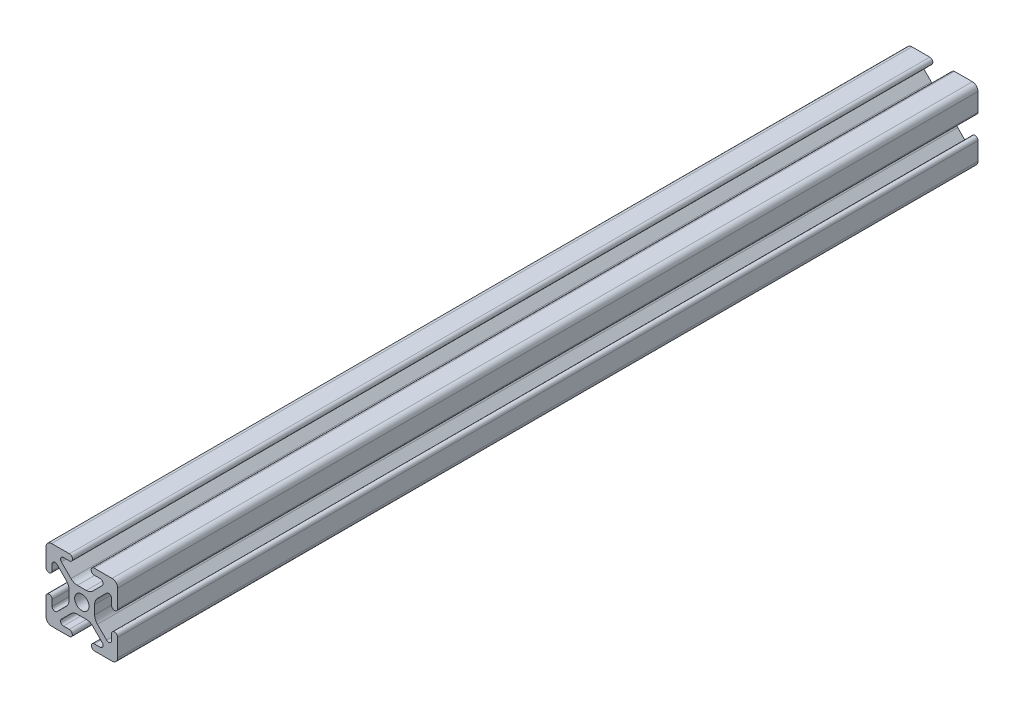
SolidWorks part; units mm, degrees
material "6005A-T61"
ref_plane "Front Plane" through (0, 0, 0) normal (0, 0, 1) x (1, 0, 0)
ref_plane "Top Plane" through (0, 0, 0) normal (0, 1, 0) x (1, 0, 0)
ref_plane "Right Plane" through (0, 0, 0) normal (1, 0, 0) x (0, 0, -1)
sketch "Sketch1" plane through (0, 0, 0) normal (0, 0, 1) x (1, 0, 0)
  line L0 (-8.6363, 7.1116) -> (-5.4322, 3.9121)
  line L1 (-4.455, 1.5554) -> (-4.455, -1.5554)
  line L2 (-5.4322, -3.9121) -> (-8.6363, -7.1116)
  line L3 (-10.36, -6.3969) -> (-10.36, -4.32)
  line L4 (-12.5, -4.32) -> (-12.5, -8.6518)
  line L5 (-12.5, -8.6518) -> (-12.5, -10.5371)
  line L6 (-10.5371, -12.5) -> (-8.4416, -12.5)
  line L7 (-8.4416, -12.5) -> (-4.3879, -12.5)
  line L8 (-4.3879, -10.36) -> (-6.42, -10.36)
  line L9 (-7.1337, -8.6353) -> (-3.7953, -5.3018)
  line L10 (-1.5554, -4.375) -> (1.5554, -4.375)
  line L11 (10.36, 4.32) -> (10.36, 6.3969)
  line L12 (12.5, 7.9913) -> (12.5, 4.32)
  line L13 (12.5, 10.5371) -> (12.5, 7.9913)
  line L14 (4.32, 12.5) -> (10.5371, 12.5)
  line L16 (6.42, 10.36) -> (4.32, 10.36)
  line L17 (3.7953, 5.3018) -> (7.1337, 8.6353)
  line L18 (7.1337, -8.6353) -> (3.7953, -5.3018)
  line L19 (4.3879, -10.36) -> (6.42, -10.36)
  line L20 (8.4416, -12.5) -> (4.3879, -12.5)
  line L21 (10.5371, -12.5) -> (8.4416, -12.5)
  line L22 (12.5, -8.6518) -> (12.5, -10.5371)
  line L23 (12.5, -4.32) -> (12.5, -8.6518)
  line L24 (10.36, -6.3969) -> (10.36, -4.32)
  line L25 (5.4322, -3.9121) -> (8.6363, -7.1116)
  line L26 (4.455, 1.5554) -> (4.455, -1.5554)
  line L27 (8.6363, 7.1116) -> (5.4322, 3.9121)
  line L28 (1.5554, 4.375) -> (-1.5554, 4.375)
  line L29 (-3.7953, 5.3018) -> (-7.1337, 8.6353)
  line L30 (-6.42, 10.36) -> (-4.32, 10.36)
  line L32 (-4.32, 12.5) -> (-10.5371, 12.5)
  line L33 (-12.5, 10.5371) -> (-12.5, 7.9913)
  line L34 (-12.5, 7.9913) -> (-12.5, 4.32)
  line L35 (-10.36, 4.32) -> (-10.36, 6.3969)
  line L36 (-15.7693, 0) -> (12.5, 0) construction
  line L37 (0, 13.9334) -> (0, -12.3541) construction
  circle A0 centre (0, 0) radius 2.5
  arc A1 (-8.6363, 7.1116) -> (-10.36, 6.3969) centre (-9.35, 6.3969) ccw
  arc A2 (-4.455, 1.5554) -> (-5.4322, 3.9121) centre (-7.7855, 1.5554) ccw
  arc A3 (-5.4322, -3.9121) -> (-4.455, -1.5554) centre (-7.7855, -1.5554) ccw
  arc A4 (-10.36, -6.3969) -> (-8.6363, -7.1116) centre (-9.35, -6.3969) ccw
  arc A5 (-10.36, -4.32) -> (-12.5, -4.32) centre (-11.43, -4.32) ccw
  arc A6 (-12.5, -10.5371) -> (-10.5371, -12.5) centre (-10.5371, -10.5371) ccw
  arc A7 (-4.3879, -12.5) -> (-4.3879, -10.36) centre (-4.3879, -11.43) ccw
  arc A8 (-7.1337, -8.6353) -> (-6.42, -10.36) centre (-6.42, -9.35) ccw
  arc A9 (-1.5554, -4.375) -> (-3.7953, -5.3018) centre (-1.5554, -7.545) ccw
  arc A10 (12.5, 4.32) -> (10.36, 4.32) centre (11.43, 4.32) cw
  arc A11 (10.5371, 12.5) -> (12.5, 10.5371) centre (10.5371, 10.5371) cw
  arc A12 (4.32, 10.36) -> (4.32, 12.5) centre (4.32, 11.43) cw
  arc A13 (6.42, 10.36) -> (7.1337, 8.6353) centre (6.42, 9.35) cw
  arc A14 (3.7953, 5.3018) -> (1.5554, 4.375) centre (1.5554, 7.545) cw
  arc A15 (1.5554, -4.375) -> (3.7953, -5.3018) centre (1.5554, -7.545) cw
  arc A16 (7.1337, -8.6353) -> (6.42, -10.36) centre (6.42, -9.35) cw
  arc A17 (4.3879, -12.5) -> (4.3879, -10.36) centre (4.3879, -11.43) cw
  arc A18 (12.5, -10.5371) -> (10.5371, -12.5) centre (10.5371, -10.5371) cw
  arc A19 (10.36, -4.32) -> (12.5, -4.32) centre (11.43, -4.32) cw
  arc A20 (10.36, -6.3969) -> (8.6363, -7.1116) centre (9.35, -6.3969) cw
  arc A21 (5.4322, -3.9121) -> (4.455, -1.5554) centre (7.7855, -1.5554) cw
  arc A22 (4.455, 1.5554) -> (5.4322, 3.9121) centre (7.7855, 1.5554) cw
  arc A23 (8.6363, 7.1116) -> (10.36, 6.3969) centre (9.35, 6.3969) cw
  arc A24 (-3.7953, 5.3018) -> (-1.5554, 4.375) centre (-1.5554, 7.545) ccw
  arc A25 (-6.42, 10.36) -> (-7.1337, 8.6353) centre (-6.42, 9.35) ccw
  arc A26 (-4.32, 10.36) -> (-4.32, 12.5) centre (-4.32, 11.43) ccw
  arc A27 (-10.5371, 12.5) -> (-12.5, 10.5371) centre (-10.5371, 10.5371) ccw
  arc A28 (-12.5, 4.32) -> (-10.36, 4.32) centre (-11.43, 4.32) ccw
  dimension "D4" = 14.86
  dimension "D5" = 2.14
  dimension "D6" = 6.5
  dimension "D7" = 8.75
  dimension "D8" = 1.01
  dimension "D9" = 3.17
  dimension "D14" = 5
  dimension "D1" = 25
  dimension "D2" = 8.91
  dimension "D3" = 12.5
  dimension "D12" = 2.14
extrude "Extrude1" add sketch "Sketch1" against normal blind 300
equation "\"WallThickness\"= 0.5cm"
equation "\"BottomPlateX\"= 3ft"
equation "\"BottomPlateZ\"= 2ft"
equation "\"BottomPlateHoleD\"=((\"ArmPlateX\")^2+(\"ArmPlateDepth\")^2)^.5+ 10mm"
equation "\"ActuatorPinD\"= 6.35mm"
equation "\"ActuatorPinL\"= 15cm"
equation "\"Box-X\"= 40cm"
equation "\"Box-Z\"= 20cm"
equation "\"Box-Y\"= 30cm"
equation "\"ArmPlateThickness\"= .125in"
equation "\"ArmPlateX\"= 18in"
equation "\"ArmPlateDepth\"= 7.1875in"
equation "\"DCMotor1D\"= 65mm"
equation "\"DCMotor1L\"= 215mm"
equation "\"DCMotor1ShaftL\"= 30mm"
equation "\"DCMotor2X\"= 68mm"
equation "\"DCMotor2D\"= 65mm"
equation "\"DCMotor2L\"= 208mm"
equation "\"DCMotor2ShaftL\"= 39mm"
equation "\"DCMotor2ShaftD\"= 15mm"
equation "\"BenchDepth\"= 5cm"
equation "\"BenchH\"= 10cm"
equation "\"BenchL\"= 15cm"
equation "\"PillowBlockW\"= 5cm"
equation "\"PillowBlockCenterH\"= \"DCMotor2X\"/2"
equation "\"EncoderRadius\"= 19mm"
equation "\"EncoderShaftL\"= 15mm"
equation "\"EncoderL\"= 33mm"
equation "\"EncoderHousingThickness\"= 7.5mm"
equation "\"TurntableID\"= 70mm"
equation "\"TurntableInner2*t\" = (\"TurntableOD\"-\"TurntableID\")*.25 - 1mm"
equation "\"TurntableInnerHoleRadius\"= \"TurntableID\"*.5 + \"TurntableInner2*t\"*.5"
equation "\"TurntableOD\"= 120mm"
equation "\"TurntableOuterHoleRadius\" = \"TurntableOD\"*.5 - ((\"TurntableOD\"-\"TurntableID\")*.25-.5mm)*.5"
equation "\"2525Height\" = 30cm"
equation "\"LENGTH@Extrude1\"=\"2525Height\""
